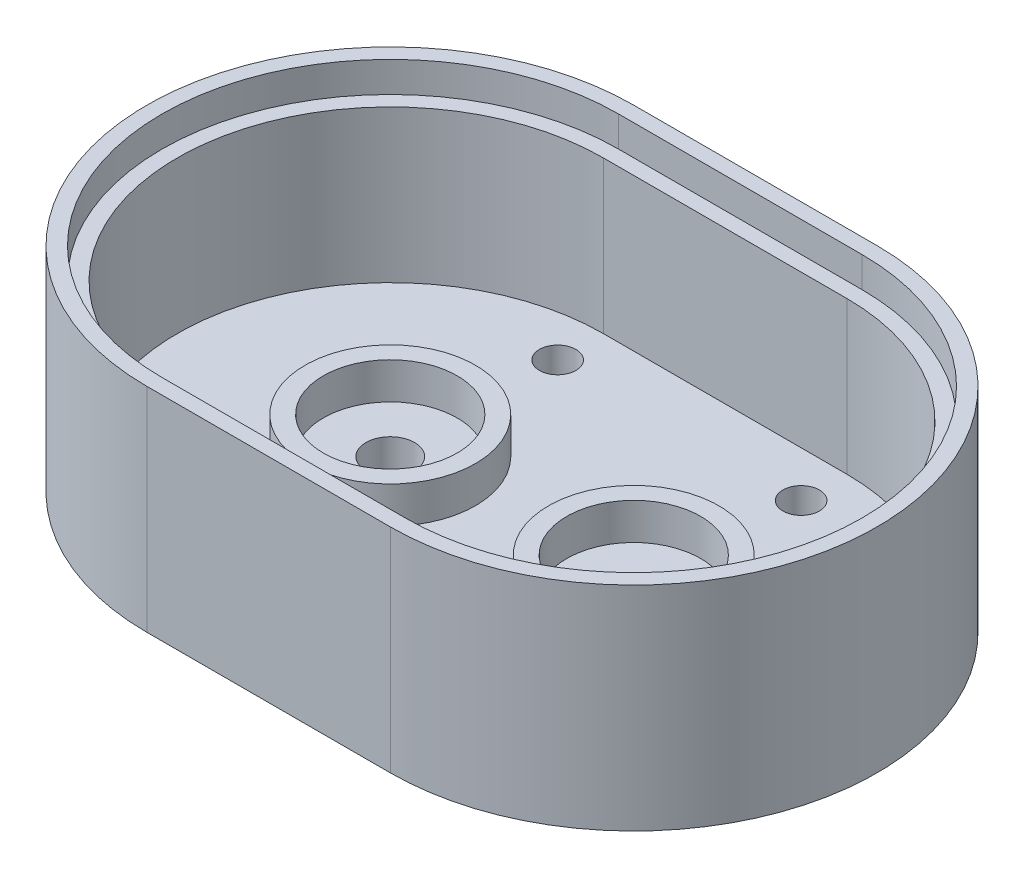
SolidWorks part; units mm, degrees
material "ABS"
ref_plane "Front" through (0, 0, 0) normal (0, 0, 1) x (1, 0, 0)
ref_plane "Top" through (0, 0, 0) normal (0, 1, 0) x (1, 0, 0)
ref_plane "Right" through (0, 0, 0) normal (1, 0, 0) x (0, 0, -1)
sketch "Croquis1" plane through (0, 0, 0) normal (0, 1, 0) x (1, 0, 0)
  line L0 (-20, 0) -> (20, 0) construction
  line L1 (-50, 0) -> (50, 0) construction
  line L2 (-20, 40) -> (20, 40)
  line L3 (-20, -40) -> (20, -40)
  line L4 (0, -50) -> (0, 50) construction
  arc A0 (-20, 40) -> (-20, -40) centre (-20, 0) ccw
  arc A1 (20, -40) -> (20, 40) centre (20, 0) ccw
  point P5 (0, 0)
  dimension "D1" = 40
  dimension "D2" = 40
extrude "Saliente-Extruir1" add sketch "Croquis1" along normal blind 5
sketch "Croquis2" plane through (0, 5, 0) normal (0, 1, 0) x (1, 0, 0)
  line L0 (-20, -35) -> (20, -35)
  line L1 (20, 35) -> (-20, 35)
  line L2 (-20, -40) -> (20, -40)
  line L3 (20, 40) -> (-20, 40)
  line L4 (-20, -40) -> (20, -40)
  line L5 (20, 40) -> (-20, 40)
  arc A0 (-20, 35) -> (-20, -35) centre (-20, 0) ccw
  arc A1 (20, -35) -> (20, 35) centre (20, 0) ccw
  arc A2 (-20, 40) -> (-20, -40) centre (-20, 0) ccw
  arc A3 (20, -40) -> (20, 40) centre (20, 0) ccw
  arc A4 (-20, 40) -> (-20, -40) centre (-20, 0) ccw
  arc A5 (20, -40) -> (20, 40) centre (20, 0) ccw
  dimension "D1" = 0
  dimension "D2" = 5
extrude "Saliente-Extruir2" add sketch "Croquis2" along normal blind 30
sketch "Croquis3" plane through (0, 35, 0) normal (0, 1, 0) x (1, 0, 0)
  line L0 (-20, -35) -> (20, -35) construction
  line L1 (20, 35) -> (-20, 35) construction
  line L2 (-20, -35) -> (20, -35)
  line L3 (20, 35) -> (-20, 35)
  line L4 (-20, -37.5) -> (20, -37.5)
  line L5 (20, 37.5) -> (-20, 37.5)
  arc A0 (20, -35) -> (20, 35) centre (20, 0) ccw construction
  arc A1 (-20, 35) -> (-20, -35) centre (-20, 0) ccw construction
  arc A2 (20, -35) -> (20, 35) centre (20, 0) ccw
  arc A3 (-20, 35) -> (-20, -35) centre (-20, 0) ccw
  arc A4 (-20, 37.5) -> (-20, -37.5) centre (-20, 0) ccw
  arc A5 (20, -37.5) -> (20, 37.5) centre (20, 0) ccw
  dimension "D1" = 2.5
extrude "Cortar-Extruir1" cut sketch "Croquis3" against normal blind 5
sketch "Croquis7" plane through (0, 0, 0) normal (0, -1, 0) x (1, 0, 0)
  circle A0 centre (-20, 0) radius 7.5
  circle A1 centre (20, 0) radius 7.5
  dimension "D1" = 15
extrude "Saliente-Extruir4" add sketch "Croquis7" along normal blind 3 draft 20
sketch "Croquis4" plane through (0, 5, 0) normal (0, 1, 0) x (1, 0, 0)
  circle A0 centre (-20, 0) radius 4
  circle A1 centre (20, 0) radius 4
  dimension "D1" = 8
extrude "Cortar-Extruir2" cut sketch "Croquis4" against normal up to next
fillet "Redondeo1" radius 1 4 edges at (-20, -3, -6.4081) (-20, 0, 7.5) (20, -3, -6.4081) (20, 0, 7.5)
sketch "Croquis9" plane through (0, 0, 0) normal (0, -1, 0) x (1, 0, 0)
  line L1 (-20, -27.5) -> (20, -27.5) construction
  line L2 (-20, -27.5) -> (-20, 27.5) construction
  line L3 (-20, 27.5) -> (20, 27.5) construction
  line L4 (20, -27.5) -> (20, 27.5) construction
  line L5 (-20, -27.5) -> (20, 27.5) construction
  line L6 (-20, 27.5) -> (20, -27.5) construction
  circle A0 centre (20, 27.5) radius 6.5
  circle A1 centre (-20, 27.5) radius 6.5
  circle A2 centre (-20, -27.5) radius 6.5
  circle A3 centre (20, -27.5) radius 6.5
  point P0 (0, 0)
  dimension "D3" = 13
  dimension "D1" = 40
  dimension "D2" = 55
extrude "Saliente-Extruir5" add sketch "Croquis9" along normal blind 3
fillet "Redondeo2" radius 1 8 edges at (-20, 0, -21) (-20, -3, -34) (20, 0, -21) (20, -3, -34) (20, 0, 34) (20, -3, 21) (-20, 0, 34) (-20, -3, 21)
sketch "Croquis8" plane through (0, 5, 0) normal (0, 1, 0) x (1, 0, 0)
  line L1 (-20, -27.5) -> (20, -27.5) construction
  line L2 (-20, -27.5) -> (-20, 27.5) construction
  line L3 (-20, 27.5) -> (20, 27.5) construction
  line L4 (20, -27.5) -> (20, 27.5) construction
  line L5 (-20, -27.5) -> (20, 27.5) construction
  line L6 (-20, 27.5) -> (20, -27.5) construction
  circle A1 centre (-20, 0) radius 20 construction
  circle A2 centre (20, 0) radius 20 construction
  circle A3 centre (-20, 27.5) radius 3
  circle A4 centre (20, 27.5) radius 3
  circle A5 centre (20, -27.5) radius 3
  circle A6 centre (-20, -27.5) radius 3
  point P7 (0, 0)
  dimension "D3" = 6
  dimension "D1" = 40
  dimension "D2" = 55
extrude "Cortar-Extruir3" cut sketch "Croquis8" against normal up to next
sketch "Croquis10" plane through (0, 5, 0) normal (0, 1, 0) x (1, 0, 0)
  circle A0 centre (-20, 0) radius 11
  circle A1 centre (20, 0) radius 11
  circle A2 centre (-20, 0) radius 14
  circle A3 centre (20, 0) radius 14
  dimension "D1" = 22
  dimension "D2" = 3
extrude "Saliente-Extruir6" add sketch "Croquis10" along normal blind 6
